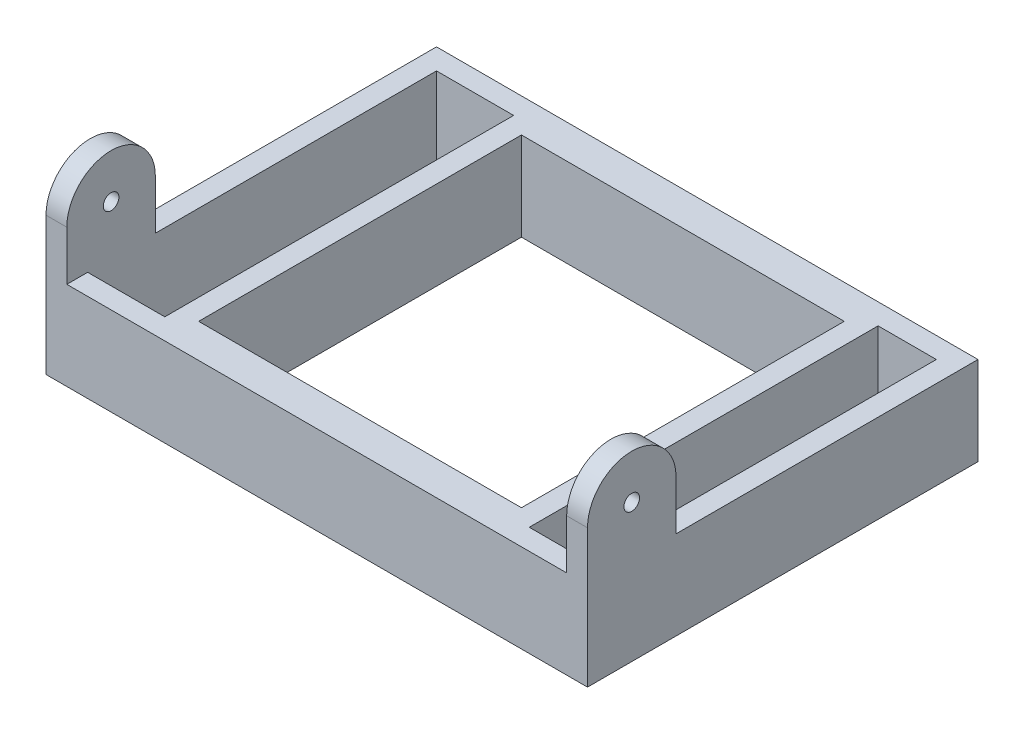
SolidWorks part; units mm, degrees
ref_plane "前视基准面" through (0, 0, 0) normal (0, 0, 1) x (1, 0, 0)
ref_plane "上视基准面" through (0, 0, 0) normal (0, 1, 0) x (1, 0, 0)
ref_plane "右视基准面" through (0, 0, 0) normal (1, 0, 0) x (0, 0, -1)
sketch "草图1" plane through (0, 0, 0) normal (0, 1, 0) x (1, 0, 0)
  line L0 (-24.9824, 67.0993) -> (-24.9824, -7.9007)
  line L6 (79.0176, -7.9007) -> (79.0176, 67.0993)
  line L7 (79.0176, 67.0993) -> (-24.9824, 67.0993)
  line L8 (-20.9824, 63.0993) -> (-6.1685, 63.0993)
  line L9 (-2.1685, 60.5993) -> (59.8315, 60.5993) construction
  line L10 (-2.1685, 60.5993) -> (-2.1685, -1.4007) construction
  line L12 (59.8315, 60.5993) -> (59.8315, -1.4007) construction
  line L13 (-2.1685, 60.5993) -> (59.8315, -1.4007) construction
  line L14 (-2.1685, -1.4007) -> (59.8315, 60.5993) construction
  line L20 (-6.1685, 63.0993) -> (-6.1685, -3.9007)
  line L22 (-2.1685, 60.5993) -> (-2.1685, -1.4007)
  line L24 (59.8315, 60.5993) -> (59.8315, -1.4007)
  line L26 (63.8315, 63.0993) -> (63.8315, -3.9007)
  line L27 (63.8315, 63.0993) -> (75.0176, 63.0993)
  line L28 (-20.9824, -3.9007) -> (-6.1685, -3.9007)
  line L30 (75.0176, -3.9007) -> (63.8315, -3.9007)
  line L32 (-20.9824, 63.0993) -> (-20.9824, -3.9007)
  line L33 (75.0176, 63.0993) -> (75.0176, -3.9007)
  line L34 (-24.9824, -7.9007) -> (79.0176, -7.9007)
  line L35 (-2.1685, -1.4007) -> (59.8315, -1.4007)
  line L36 (-2.1685, 60.5993) -> (59.8315, 60.5993)
  point P3 (0, 0)
  point P7 (-24.9824, 29.5993)
  point P12 (28.8315, 29.5993)
  point P15 (28.8315, 60.5993)
  point P20 (29.9131, 0.0003)
  point P23 (-6.452, 33.0003)
  point P28 (67.5632, 33.0003)
  dimension "D2" = 4
  dimension "D3" = 96
  dimension "D4" = 75
  dimension "D5" = 62
  dimension "D6" = 62
  dimension "D7" = 4
  dimension "D8" = 4
  dimension "D9" = 4
  dimension "D10" = 4
  dimension "D11" = 4
  dimension "D12" = 4
extrude "凸台-拉伸3" add sketch "草图1" along normal blind 17
sketch "草图3" plane through (0, 17, 0) normal (0, 1, 0) x (1, 0, 0)
  line L0 (-20.9824, 63.0993) -> (-20.9824, -3.9007) construction
  line L1 (-24.9824, -7.9007) -> (-20.9824, -7.9007)
  line L2 (-24.9824, -7.9007) -> (-24.9824, 9.0993)
  line L3 (-24.9824, 9.0993) -> (-20.9824, 9.0993)
  line L4 (-20.9824, -7.9007) -> (-20.9824, 9.0993)
  line L5 (-24.9824, -7.9007) -> (-20.9824, 9.0993) construction
  line L6 (-24.9824, 9.0993) -> (-20.9824, -7.9007) construction
  line L7 (75.0176, -3.9007) -> (75.0176, 63.0993) construction
  line L8 (79.0176, -7.9007) -> (75.0176, -7.9007)
  line L9 (79.0176, -7.9007) -> (79.0176, 9.0993)
  line L10 (79.0176, 9.0993) -> (75.0176, 9.0993)
  line L11 (75.0176, -7.9007) -> (75.0176, 9.0993)
  line L12 (79.0176, -7.9007) -> (75.0176, 9.0993) construction
  line L13 (79.0176, 9.0993) -> (75.0176, -7.9007) construction
  point P4 (-22.9824, 0.5993)
  point P12 (77.0176, 0.5993)
  dimension "D1" = 17
extrude "凸台-拉伸4" add sketch "草图3" along normal blind 18
sketch "草图4" plane through (-24.9824, 0, 0) normal (-1, 0, 0) x (0, 0, 1)
  line L0 (7.9007, 35) -> (7.9007, 0) construction
  line L1 (-9.0993, 35) -> (7.9007, 35) construction
  line L2 (-9.0993, 35) -> (-9.0993, 18) construction
  line L3 (-9.0993, 18) -> (7.9007, 18) construction
  line L4 (7.9007, 35) -> (7.9007, 18) construction
  line L5 (-9.0993, 35) -> (7.9007, 18) construction
  line L6 (-9.0993, 18) -> (7.9007, 35) construction
  line L7 (-9.0993, 26.5) -> (-9.0993, 35)
  line L8 (-9.0993, 35) -> (7.9007, 35)
  line L9 (7.9007, 35) -> (7.9007, 26.5)
  arc A0 (-9.0993, 26.5) -> (7.9007, 26.5) centre (-0.5993, 26.5) cw
  circle A1 centre (-0.5993, 26.5) radius 1.5
  point P4 (-0.5993, 26.5)
  point P8 (-9.0993, 26.5)
  point P9 (7.9007, 26.5)
  point P10 (-0.5993, 35)
  line M3 (7.9007, 0) -> (7.9007, 35)
  line M4 (7.9007, 35) -> (-9.0993, 35)
  line M5 (-9.0993, 35) -> (-9.0993, 17)
  dimension "D1" = 17
extrude "切除-拉伸2" cut sketch "草图4" against normal blind 150 contours A0 L8 M5 | A0 M4 M3 | A1
